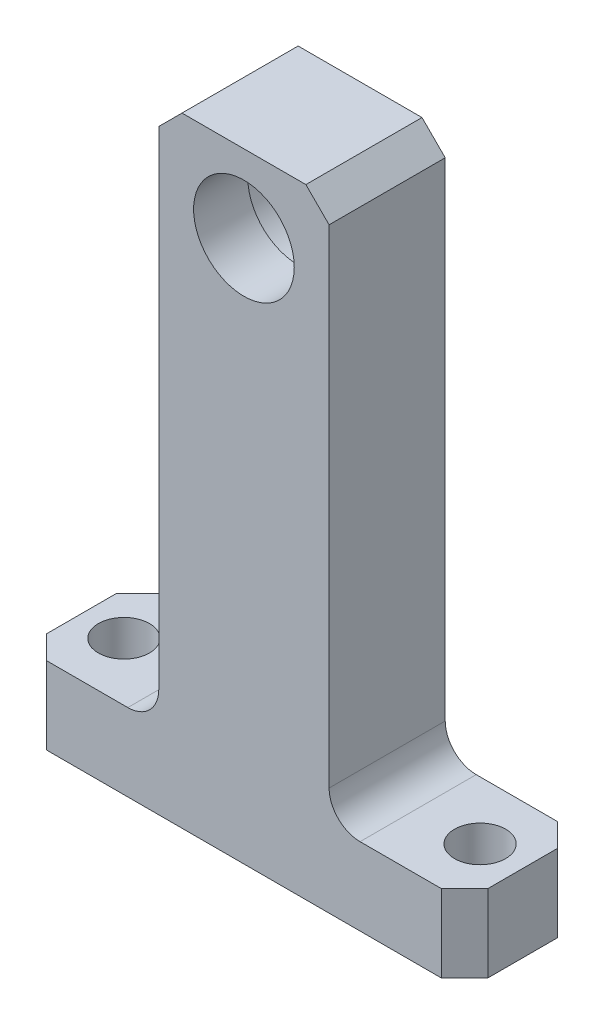
SolidWorks part; units mm, degrees
material "6061-T6 (SS)"
ref_plane "Front Plane" through (0, 0, 0) normal (0, 0, 1) x (1, 0, 0)
ref_plane "Top Plane" through (0, 0, 0) normal (0, 1, 0) x (1, 0, 0)
ref_plane "Right Plane" through (0, 0, 0) normal (1, 0, 0) x (0, 0, -1)
sketch "LOC - Holes" plane through (0, 0, 0) normal (0, 1, 0) x (1, 0, 0)
  line L0 (0, 0) -> (-12.5, 0) construction
  line L1 (-12.5, 0) -> (-23, 0) construction
  line L4 (0, 0) -> (12.5, 0) construction
  line L5 (12.5, 0) -> (23, 0) construction
  dimension "D1" = 12.5
  dimension "D2" = 23
  dimension "D3" = 12.5
  dimension "D4" = 23
sketch "Sketch1" plane through (0, 0, 0) normal (0, 0, 1) x (1, 0, 0)
  line L0 (-11, 0) -> (11, 0)
  line L1 (-11, 0) -> (-11, -70)
  line L2 (-11, -70) -> (-28.5, -70)
  line L3 (-28.5, -70) -> (-28.5, -80)
  line L4 (-28.5, -80) -> (28.5, -80)
  line L5 (28.5, -80) -> (28.5, -70)
  line L6 (11, 0) -> (11, -70)
  line L7 (11, -70) -> (28.5, -70)
  dimension "D1" = 22
  dimension "D2" = 10
  dimension "D3" = 57
  dimension "D4" = 80
extrude "Boss-Extrude1" add sketch "Sketch1" along normal mid plane 15
fillet "Fillet1" radius 4 2 edges at (11, -70, 0) (-11, -70, 0)
hole_wizard "M6 Clearance Hole1" positions "Sketch7" profile "Sketch6" hole size "M6" standard "ANSI Metric" end condition up to next
sketch "Sketch7" plane through (0, -80, 0) normal (0, -1, 0) x (-1, 0, 0)
  point P35 (23, 0)
  point P38 (-23, 0)
sketch "Sketch6" plane through (-23, -80, 0) normal (1, 0, 0) x (0, 0, -1)
  line L0 (0, 0) -> (0, 10)
  line L1 (0, 10) -> (3.3, 10)
  line L2 (3.3, 10) -> (3.3, 0)
  line L5 (3.3, 0) -> (0, 0)
  line L11 (0, -6.35) -> (0, 107.95) construction
  dimension "Thru Hole Dia." = 6.6
  dimension "Thru Hole Depth" = 10
hole_wizard "Ø4.0 (4) Diameter Hole1" positions "Sketch4" profile "Sketch3" hole size "Ø4.0" standard "ANSI Metric"
sketch "Sketch4" plane through (0, -80, 0) normal (0, -1, 0) x (-1, 0, 0)
  point P0 (12.5, 0)
sketch "Sketch3" plane through (-12.5, -80, 0) normal (1, 0, 0) x (0, 0, -1)
  line L0 (0, 0) -> (0, 9.2017)
  line L1 (0, 9.2017) -> (2, 8)
  line L2 (2, 8) -> (2, 0)
  line L5 (2, 0) -> (0, 0)
  line L10 (0, 9.2017) -> (-2, 8) construction
  line L11 (0, -6.35) -> (0, 107.95) construction
  dimension "Hole Dia." = 4
  dimension "Hole Depth" = 8
  dimension "Drill Angle" = 118
sketch "Sketch5" plane through (0, -80, 0) normal (0, -1, 0) x (1, 0, 0)
  line L0 (10, 0) -> (15, 0) construction
  line L1 (10, 2) -> (15, 2)
  line L2 (10, -2) -> (15, -2)
  arc A0 (10, 2) -> (10, -2) centre (10, 0) ccw
  arc A1 (15, -2) -> (15, 2) centre (15, 0) ccw
  point P2 (12.5, 0)
  dimension "D1" = 2
  dimension "D2" = 5
extrude "Cut-Extrude1" cut sketch "Sketch5" against normal blind 8
chamfer "Chamfer1" distance 3 angle 45 4 edges at (28.5, -75, 7.5) (28.5, -75, -7.5) (-28.5, -75, -7.5) (-28.5, -75, 7.5)
sketch "Sketch12" plane through (0, 0, 0) normal (0, 0, 1) x (1, 0, 0)
  line L0 (0, -80) -> (0, -10) construction
  line L1 (-28.5, -80) -> (28.5, -80) construction
  circle A0 centre (0, -10) radius 7.525
  dimension "D1" = 15.05
extrude "Cut-Extrude6" cut sketch "Sketch12" along normal offset from surface 7 and the other way through all up to face at (0, -57.3657, 7.5)
sketch "Sketch13" plane through (0, 0, 0) normal (0, 0, 1) x (1, 0, 0)
  circle A0 centre (0, -10) radius 6.5
  dimension "D1" = 13
extrude "Cut-Extrude7" cut sketch "Sketch13" against normal through all and the other way through all
chamfer "Chamfer3" distance 3 angle 45 2 edges at (-11, 0, 0) (11, 0, 0)
